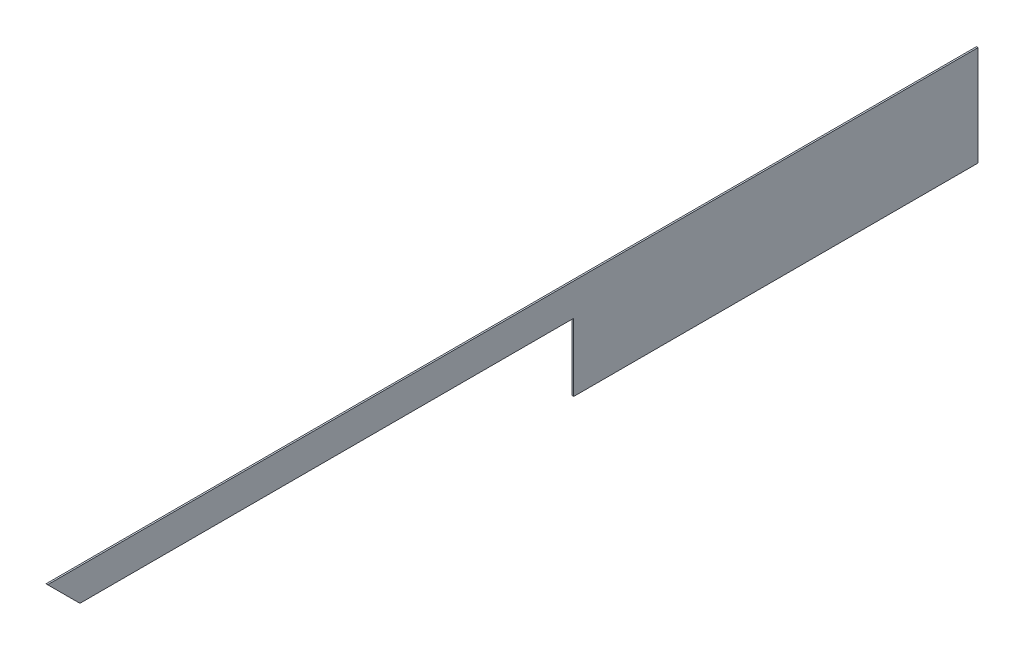
SolidWorks part; units mm, degrees
ref_plane "Front Plane" through (0, 0, 0) normal (0, 0, 1) x (1, 0, 0)
ref_plane "Top Plane" through (0, 0, 0) normal (0, 1, 0) x (1, 0, 0)
ref_plane "Right Plane" through (0, 0, 0) normal (1, 0, 0) x (0, 0, -1)
sketch "Sketch2" plane through (0, 0, 0) normal (1, 0, 0) x (0, 0, -1)
  line L0 (288.35, 31) -> (-288.35, 31)
  line L1 (288.35, 31) -> (288.35, -31)
  line L2 (288.35, -31) -> (37.75, -31)
  line L4 (37.75, -31) -> (37.75, 11)
  line L5 (37.75, 11) -> (-261.2822, 11)
  line L8 (-261.2822, 11) -> (-268.3177, 11)
  line L9 (-268.3177, 11) -> (-288.35, 31)
  point P4 (0, 0)
  point P9 (0, 0)
  point P10 (0, 0)
  point P11 (0, 0)
  dimension "D1" = 576.7
  dimension "D2" = 28.3071
  dimension "D4" = 306.0677
  dimension "D5" = 42
  dimension "D6" = 250.6
  dimension "D7" = 62
extrude "Boss-Extrude1" add sketch "Sketch2" along normal blind 1
